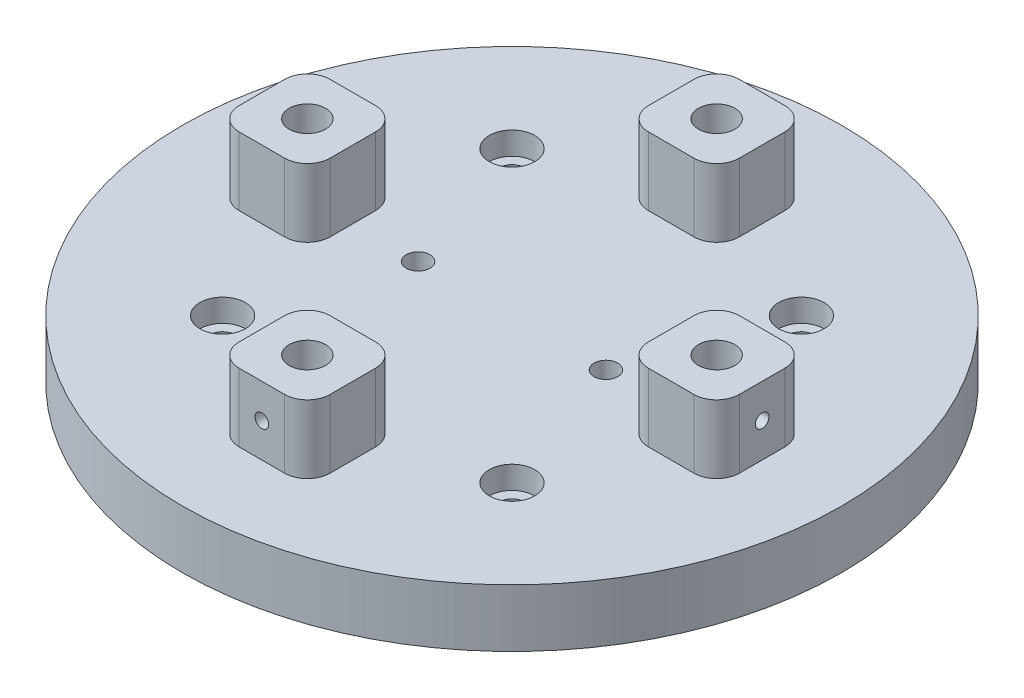
SolidWorks part; units mm, degrees
ref_plane "Front Plane" through (0, 0, 0) normal (0, 0, 1) x (1, 0, 0)
ref_plane "Top Plane" through (0, 0, 0) normal (0, 1, 0) x (1, 0, 0)
ref_plane "Right Plane" through (0, 0, 0) normal (1, 0, 0) x (0, 0, -1)
sketch "Sketch1" plane through (0, 0, 0) normal (0, 1, 0) x (1, 0, 0)
  circle A0 centre (0, 0) radius 72.5
  dimension "D1" = 145
extrude "Boss-Extrude1" add sketch "Sketch1" along normal blind 12.7
hole_wizard "CBORE for M5 Hex Head Bolt2" positions "Sketch6" profile "Sketch7" counterbore size "M5" standard "ANSI Metric" end condition up to next
sketch "Sketch6" plane through (0, 12.7, 0) normal (0, 1, 0) x (1, 0, 0)
  line L0 (0, 0) -> (31.8198, 31.8198) construction
  line L2 (0, 0) -> (0, -50000) construction
  line L3 (0, 0) -> (-31.8198, -31.8198) construction
  point P0 (31.8198, 31.8198)
  point P17 (31.8198, -31.8198)
  point P18 (-31.8198, -31.8198)
  point P19 (-31.8198, 31.8198)
  dimension "D1" = 45
  dimension "D2" = 45
  dimension "D3" = 4
sketch "Sketch7" plane through (31.8198, 12.7, -31.8198) normal (1, 0, 0) x (0, 0, 1)
  line L0 (0, 0) -> (0, 12.7)
  line L1 (0, 12.7) -> (2.75, 12.7)
  line L3 (2.75, 12.7) -> (2.75, 5)
  line L4 (2.75, 5) -> (5, 5)
  line L5 (5, 5) -> (5, 0)
  line L7 (5, 0) -> (0, 0)
  line L11 (0, -6.35) -> (0, 107.95) construction
  dimension "Thru Hole Dia." = 5.5
  dimension "Thru Hole Depth" = 12.7
  dimension "C'Bore Dia." = 10
  dimension "C'Bore Depth" = 5
sketch "Sketch22" plane through (0, 0, 0) normal (0, -1, 0) x (1, 0, 0)
  circle A0 centre (0, 0) radius 15
  dimension "D1" = 30
extrude "Boss-Extrude3" add sketch "Sketch22" along normal blind 38
sketch "Sketch11" plane through (0, 12.7, 0) normal (0, 1, 0) x (1, 0, 0)
  line L1 (-10, -35) -> (10, -35)
  line L2 (-10, -35) -> (-10, -55)
  line L3 (-10, -55) -> (10, -55)
  line L4 (10, -35) -> (10, -55)
  line L5 (-10, -35) -> (10, -55) construction
  line L6 (-10, -55) -> (10, -35) construction
  point P0 (0, -45)
  dimension "D1" = 45
  dimension "D2" = 20
extrude "Boss-Extrude2" add sketch "Sketch11" along normal blind 15
sketch "Sketch24" plane through (0, 27.7, 0) normal (0, 1, 0) x (1, 0, 0)
  line L0 (0, -45) -> (10, -45) construction
  line L1 (10, -55) -> (10, -35) construction
  line L2 (0, -45) -> (0, -35) construction
  line L3 (10, -35) -> (-10, -35) construction
  circle A0 centre (0, -45) radius 4
  dimension "D1" = 8
extrude "Cut-Extrude7" cut sketch "Sketch24" against normal blind 15
fillet "Fillet1" radius 5 4 edges at (10, 20.2, 35) (-10, 20.2, 35) (-10, 20.2, 55) (10, 20.2, 55)
sketch "Sketch18" plane through (0, 0, 55) normal (0, 0, 1) x (1, 0, 0)
  line L0 (-5, 27.7) -> (5, 27.7) construction
  line L1 (0, 27.7) -> (0, 12.7) construction
  line L2 (-5, 12.7) -> (5, 12.7) construction
  circle A0 centre (0, 20.2) radius 1.5
  dimension "D1" = 3
extrude "Cut-Extrude4" cut sketch "Sketch18" against normal up to next
pattern_circular "CirPattern2" count 4 over 360 about axis through (0, 0, 0) along (0, 1, 0) of "Boss-Extrude2", "Cut-Extrude4", "Fillet1", "Cut-Extrude7"
sketch "Sketch25" plane through (0, 12.7, 0) normal (0, 1, 0) x (1, 0, 0)
  line L0 (0, 72.5) -> (0, -72.5) construction
  circle A0 centre (20.65, 0) radius 2.6
  circle A1 centre (0, 0) radius 72.5 construction
  circle A2 centre (-20.65, 0) radius 2.6
  dimension "D1" = 5.2
  dimension "D2" = 20.65
extrude "Cut-Extrude8" cut sketch "Sketch25" against normal through all
sketch "Sketch26" plane through (0, 0, 0) normal (0, -1, 0) x (1, 0, 0)
  line L0 (0, 72.5) -> (0, -72.5) construction
  circle A0 centre (20.65, 0) radius 5
  circle A1 centre (0, 0) radius 72.5 construction
  circle A2 centre (-20.65, 0) radius 5
  dimension "D1" = 10
extrude "Cut-Extrude9" cut sketch "Sketch26" against normal blind 3.5
